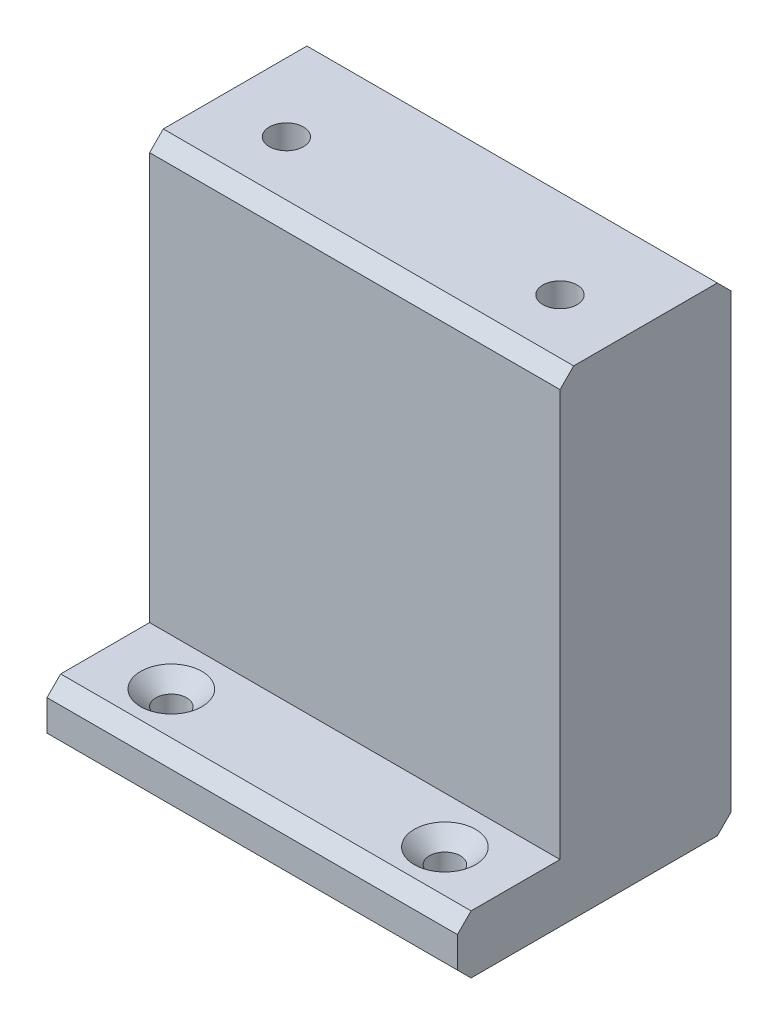
SolidWorks part; units mm, degrees
ref_plane "Front Plane" through (0, 0, 0) normal (0, 0, 1) x (1, 0, 0)
ref_plane "Top Plane" through (0, 0, 0) normal (0, 1, 0) x (1, 0, 0)
ref_plane "Right Plane" through (0, 0, 0) normal (1, 0, 0) x (0, 0, -1)
sketch "Sketch1" plane through (0, 0, 0) normal (0, 1, 0) x (1, 0, 0)
  line L1 (-30, -20) -> (30, -20)
  line L2 (-30, -20) -> (-30, 20)
  line L3 (-30, 20) -> (30, 20)
  line L4 (30, -20) -> (30, 20)
  line L5 (-30, -20) -> (30, 20) construction
  line L6 (-30, 20) -> (30, -20) construction
  point P0 (0, 0)
  dimension "D1" = 60
  dimension "D2" = 40
extrude "Boss-Extrude1" add sketch "Sketch1" along normal blind 70
sketch "Sketch2" plane through (30, 0, 0) normal (1, 0, 0) x (0, 0, -1)
  line L0 (-20, 70) -> (20, 70) construction
  line L1 (-20, 8.5) -> (-5, 8.5)
  line L2 (-20, 8.5) -> (-20, 70)
  line L3 (-20, 70) -> (-5, 70)
  line L4 (-5, 8.5) -> (-5, 70)
  line L5 (-20, 8.5) -> (-5, 70) construction
  line L6 (-20, 70) -> (-5, 8.5) construction
  line L7 (-20, 0) -> (20, 0) construction
  line L8 (-20, 70) -> (-20, 0) construction
  point P0 (-12.5, 39.25)
  dimension "D1" = 15
  dimension "D2" = 0
  dimension "D3" = 8.5
extrude "Cut-Extrude1" cut sketch "Sketch2" against normal blind 90
hole_wizard "CSK for M4 SFHCS1" positions "Sketch3" profile "Sketch4" countersink size "M4" standard "ANSI Metric" end condition through all
sketch "Sketch3" plane through (0, 8.5, 0) normal (0, 1, 0) x (1, 0, 0)
  line L0 (-20, -11.825) -> (20, -11.825)
  point P1 (-20, -11.825)
  point P2 (20, -11.825)
  point P5 (0, -11.825)
  dimension "D1" = 40
  dimension "D2" = 31.825
sketch "Sketch4" plane through (-20, 8.5, 11.825) normal (1, 0, 0) x (0, 0, 1)
  line L0 (0, 0) -> (0, 8.5)
  line L1 (0, 8.5) -> (2.25, 8.5)
  line L2 (2.25, 8.5) -> (2.25, 2.23)
  line L3 (2.25, 2.23) -> (4.48, 0)
  line L5 (4.48, 0) -> (0, 0)
  line L6 (-2.25, 2.23) -> (-4.48, 0) construction
  line L11 (0, -6.35) -> (0, 107.95) construction
  dimension "Thru Hole Dia." = 4.5
  dimension "Thru Hole Depth" = 8.5
  dimension "Near C'Sink Dia." = 8.96
  dimension "Near C'Sink Angle" = 90
hole_wizard "CBORE for M5 Hex Head Bolt1" positions "Sketch5" profile "Sketch7" counterbore size "M5" standard "ANSI Metric"
sketch "Sketch5" plane through (0, 0, -20) normal (0, 0, -1) x (-1, 0, 0)
  line L1 (-20, 15) -> (20, 15)
  line L2 (-20, 15) -> (-20, 55)
  line L3 (-20, 55) -> (20, 55)
  line L4 (20, 15) -> (20, 55)
  line L5 (-20, 15) -> (20, 55) construction
  line L6 (-20, 55) -> (20, 15) construction
  line L7 (-30, 0) -> (30, 0) construction
  point P1 (20, 55)
  point P52 (-20, 15)
  point P53 (-20, 55)
  point P54 (20, 15)
  point P66 (0, 35)
  dimension "D1" = 40
  dimension "D2" = 40
  dimension "D3" = 35
sketch "Sketch7" plane through (-20, 55, -20) normal (1, 0, 0) x (0, 1, 0)
  line L0 (0, 0) -> (0, 11.3519)
  line L1 (0, 11.3519) -> (2.25, 10)
  line L2 (2.25, 10) -> (2.25, 4.2)
  line L3 (2.25, 4.2) -> (2.5, 4.2)
  line L4 (2.5, 4.2) -> (2.5, 0)
  line L5 (2.5, 0) -> (0, 0)
  line L10 (0, 11.3519) -> (-2.25, 10) construction
  line L11 (0, -6.35) -> (0, 107.95) construction
  dimension "Hole Dia." = 4.5
  dimension "Hole Depth" = 10
  dimension "C'Bore Dia." = 5
  dimension "C'Bore Depth" = 4.2
  dimension "Drill Angle" = 118
hole_wizard "CBORE for M5 Hex Head Bolt2" positions "Sketch8" profile "Sketch10" counterbore size "M5" standard "ANSI Metric"
sketch "Sketch8" plane through (0, 70, 0) normal (0, 1, 0) x (1, 0, 0)
  line L0 (-20, 5) -> (20, 5)
  line L1 (30, 20) -> (-30, 20) construction
  point P0 (-20, 5)
  point P1 (20, 5)
  point P8 (0, 5)
  dimension "D1" = 40
  dimension "D2" = 15
sketch "Sketch10" plane through (-20, 70, -5) normal (1, 0, 0) x (0, 0, 1)
  line L0 (0, 0) -> (0, 11.3519)
  line L1 (0, 11.3519) -> (2.25, 10)
  line L2 (2.25, 10) -> (2.25, 4.2)
  line L3 (2.25, 4.2) -> (2.5, 4.2)
  line L4 (2.5, 4.2) -> (2.5, 0)
  line L5 (2.5, 0) -> (0, 0)
  line L10 (0, 11.3519) -> (-2.25, 10) construction
  line L11 (0, -6.35) -> (0, 107.95) construction
  dimension "Hole Dia." = 4.5
  dimension "Hole Depth" = 10
  dimension "C'Bore Dia." = 5
  dimension "C'Bore Depth" = 4.2
  dimension "Drill Angle" = 118
sketch "Sketch13" [suppressed] plane through (0, 0, 20) normal (0, 0, 1) x (1, 0, 0)
  line L4 (30, 0) -> (30, 8.5)
  line L5 (30, 8.5) -> (-30, 8.5)
  line L6 (-30, 8.5) -> (-30, 0)
  line L7 (-30, 0) -> (30, 0)
  line L8 (30, 0) -> (30, 8.5)
  line L9 (30, 8.5) -> (-30, 8.5)
  line L10 (-30, 8.5) -> (-30, 0)
  line L11 (-30, 0) -> (30, 0)
  dimension "D1" = 0
extrude "Boss-Extrude2" [suppressed] add sketch "Sketch13" along normal blind 7.5
hole_wizard "CSK for M4 SFHCS2" [suppressed] positions "Sketch11" profile "Sketch12" countersink size "M4" standard "ANSI Metric"
sketch "Sketch11" plane through (0, 8.5, 0) normal (0, 1, 0) x (1, 0, 0)
  line L0 (-20, -18.18) -> (20, -18.18)
  point P1 (-20, -18.18)
  point P2 (20, -18.18)
  point P5 (0, -18.18)
  dimension "D1" = 38.18
  dimension "D2" = 40
sketch "Sketch12" plane through (-20, 8.5, 18.18) normal (1, 0, 0) x (0, 0, 1)
  line L0 (0, 0) -> (0, 8.5)
  line L1 (0, 8.5) -> (2.25, 8.5)
  line L2 (2.25, 8.5) -> (2.25, 2.23)
  line L3 (2.25, 2.23) -> (4.48, 0)
  line L5 (4.48, 0) -> (0, 0)
  line L6 (-2.25, 2.23) -> (-4.48, 0) construction
  line L11 (0, -6.35) -> (0, 107.95) construction
  dimension "Thru Hole Dia." = 4.5
  dimension "Thru Hole Depth" = 8.5
  dimension "Near C'Sink Dia." = 8.96
  dimension "Near C'Sink Angle" = 90
chamfer "Chamfer1" [suppressed] distance 2 angle 45
chamfer "Chamfer2" distance 2 angle 45 5 edges at (0, 0, -20) (0, 0, 20) (0, 8.5, 20) (0, 70, -20) (0, 70, 5)
